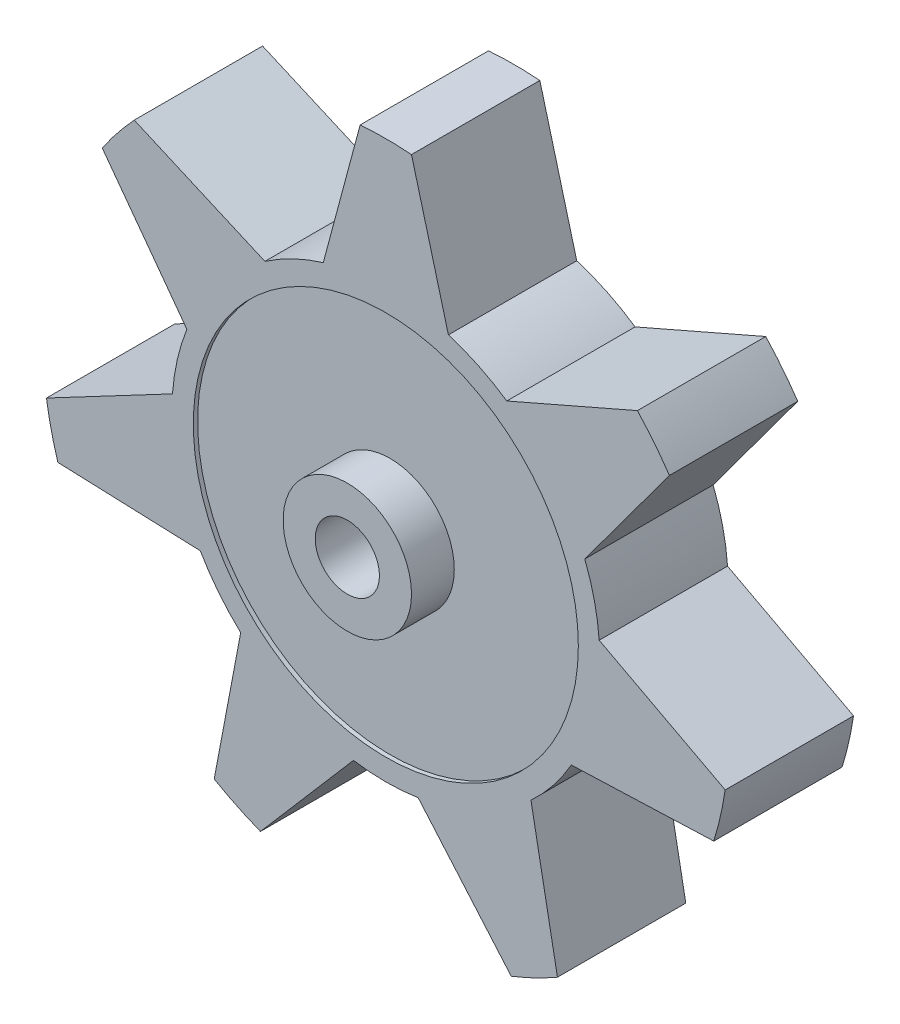
SolidWorks part; units mm, degrees
ref_plane "Front Plane" through (0, 0, 0) normal (0, 0, 1) x (1, 0, 0)
ref_plane "Top Plane" through (0, 0, 0) normal (0, 1, 0) x (1, 0, 0)
ref_plane "Right Plane" through (0, 0, 0) normal (1, 0, 0) x (0, 0, -1)
sketch "Sketch1" plane through (0, 0, 0) normal (0, 0, 1) x (1, 0, 0)
  circle A0 centre (0, 0) radius 5
  dimension "D1" = 10
extrude "Boss-Extrude1" add sketch "Sketch1" along normal blind 3
sketch "Sketch2" plane through (0, 0, 3) normal (0, 0, 1) x (1, 0, 0)
  line L0 (0, 5) -> (0, 8) construction
  line L1 (-0.6, 8) -> (0.6, 8) construction
  line L2 (-1.4624, 4.7813) -> (1.4624, 4.7813)
  line L3 (-0.6, 8) -> (-1.4624, 4.7813)
  line L4 (0.6, 8) -> (1.4624, 4.7813)
  circle A0 centre (0, 0) radius 5 construction
  arc A1 (-0.6, 8) -> (0.6, 8) centre (0, 0) cw
  point P9 (0, 8)
  point P12 (0, 4.7813)
  dimension "D1" = 3
  dimension "D2" = 75
  dimension "D3" = 75
  dimension "D4" = 1.2
extrude "Boss-Extrude2" add sketch "Sketch2" against normal up to surface (3 mm away) up to face at (5, 0, 0)
pattern_circular "CirPattern2" count 7 over 360 about axis through (0, 0, 0) along (0, 0, 1) of "Boss-Extrude2"
sketch "Sketch3" plane through (0, 0, 3) normal (0, 0, 1) x (1, 0, 0)
  circle A0 centre (0, 0) radius 4.5
  dimension "D1" = 9
extrude "Cut-Extrude1" cut sketch "Sketch3" against normal blind 0.1
sketch "Sketch4" plane through (0, 0, 2.9) normal (0, 0, 1) x (1, 0, 0)
  circle A0 centre (0, 0) radius 1.5
  dimension "D1" = 3
extrude "Boss-Extrude3" add sketch "Sketch4" along normal blind 1
sketch "Sketch5" plane through (0, 0, 3.9) normal (0, 0, 1) x (1, 0, 0)
  circle A0 centre (0, 0) radius 0.75
  dimension "D1" = 1.5
extrude "Cut-Extrude2" cut sketch "Sketch5" against normal through all
